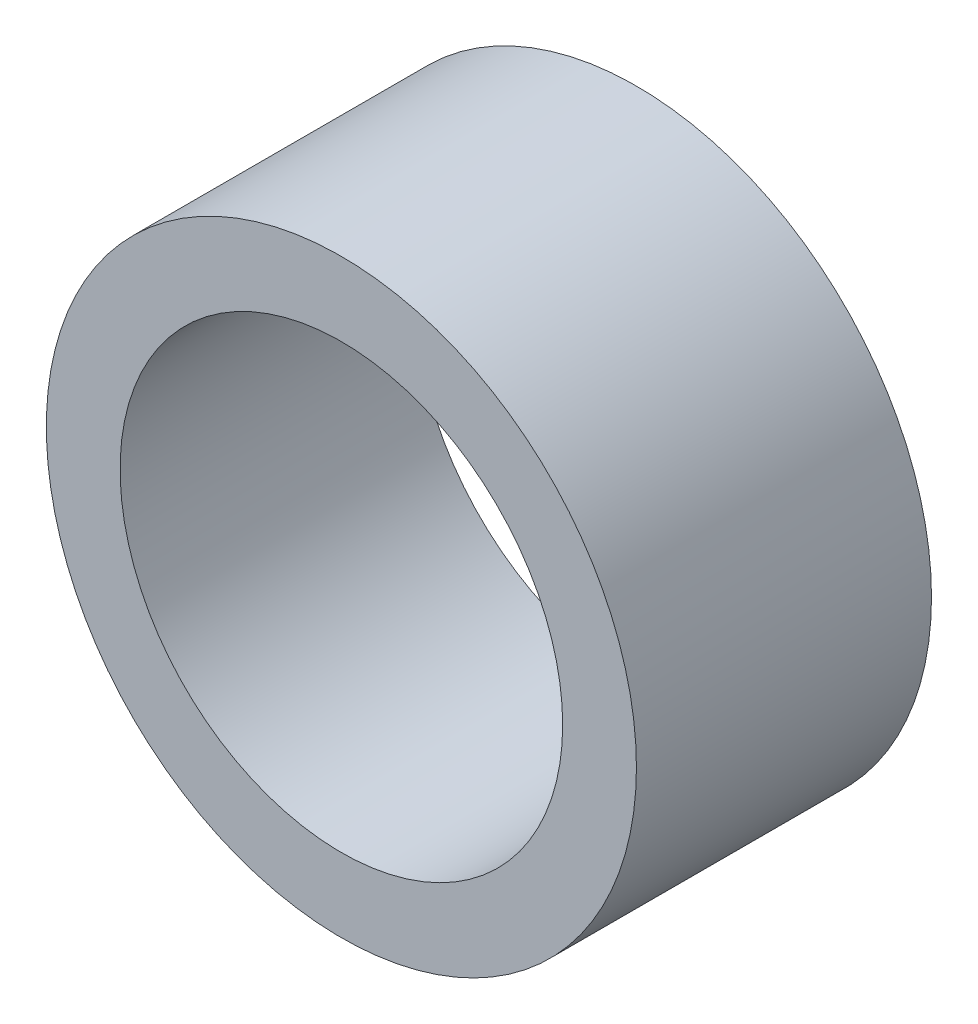
SolidWorks part; units mm, degrees
material "黄銅"
ref_plane "正面" through (0, 0, 0) normal (0, 0, 1) x (1, 0, 0)
ref_plane "平面" through (0, 0, 0) normal (0, 1, 0) x (1, 0, 0)
ref_plane "右側面" through (0, 0, 0) normal (1, 0, 0) x (0, 0, -1)
sketch "ｽｹｯﾁ1" plane through (0, 0, 0) normal (0, 0, 1) x (1, 0, 0)
  circle A0 centre (0, 0) radius 4
  dimension "D1" = 8
extrude "ﾎﾞｽ - 押し出し1" add sketch "ｽｹｯﾁ1" along normal blind 4
sketch "ｽｹｯﾁ2" plane through (0, 0, 4) normal (0, 0, 1) x (1, 0, 0)
  circle A0 centre (0, 0) radius 3
  dimension "D1" = 6
extrude "ｶｯﾄ - 押し出し1" cut sketch "ｽｹｯﾁ2" against normal through all
